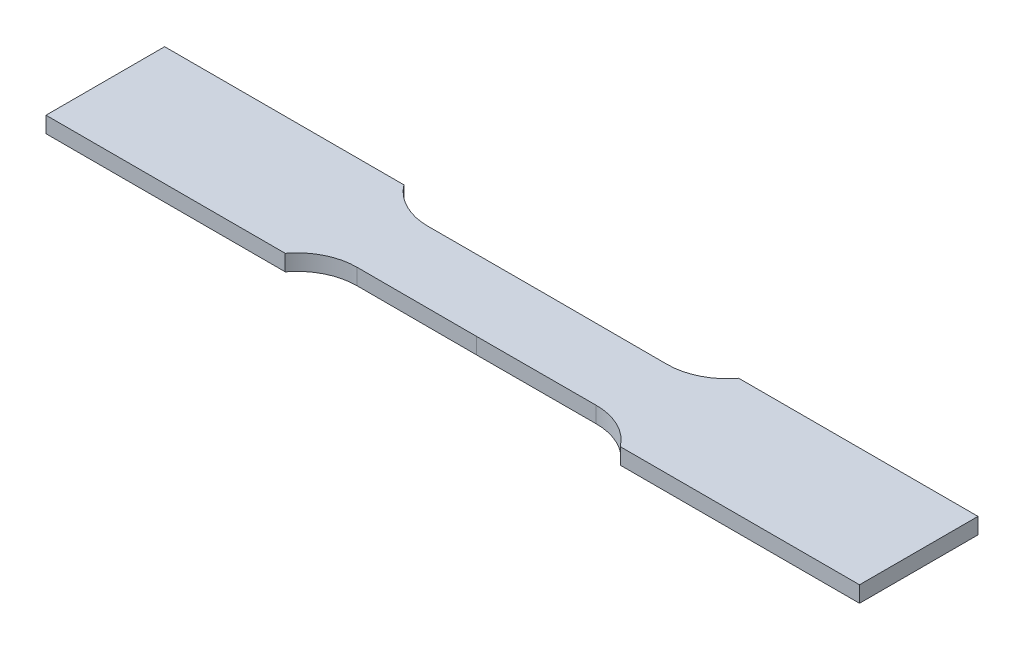
SolidWorks part; units mm, degrees
ref_plane "Front Plane" through (0, 0, 0) normal (0, 0, 1) x (1, 0, 0)
ref_plane "Top Plane" through (0, 0, 0) normal (0, 1, 0) x (1, 0, 0)
ref_plane "Right Plane" through (0, 0, 0) normal (1, 0, 0) x (0, 0, -1)
sketch "Sketch1" plane through (0, 0, 0) normal (0, 1, 0) x (1, 0, 0)
  line L3 (25, 7.405) -> (0, 7.44)
  line L4 (0, 7.44) -> (-25, 7.415)
  line L5 (-25, -7.415) -> (0, -7.44)
  line L6 (0, -7.44) -> (25, -7.405)
  line L7 (0, 7.44) -> (0, -7.44) construction
  line L8 (-25, 0) -> (25, 0) construction
  line L9 (25, 7.405) -> (25, 12.3817) construction
  line L10 (-35, 12.3984) -> (-25, 12.3984) construction
  line L11 (-25, 12.3984) -> (-25, 7.415) construction
  line L12 (-25, -12.3984) -> (-25, -7.415) construction
  line L13 (-35, 12.3984) -> (-85, 12.3984)
  line L15 (-35, -12.3984) -> (-85, -12.3984)
  line L16 (-85, 12.3984) -> (-85, -12.3984)
  line L17 (25, 12.3817) -> (35, 12.3817) construction
  line L18 (-35, -12.3984) -> (-25, -12.3984) construction
  line L19 (-25, 7.415) -> (-25, -7.415) construction
  line L20 (25, -7.405) -> (25, 7.405) construction
  line L22 (25, -7.405) -> (25, -12.3817) construction
  line L23 (25, -12.3817) -> (35, -12.3817) construction
  line L24 (35, 12.3817) -> (85, 12.3817)
  line L26 (35, -12.3817) -> (85, -12.3817)
  line L27 (85, 12.3817) -> (85, -12.3817)
  arc A0 (-35, 12.3984) -> (-25, 7.415) centre (-25.0125, 19.915) ccw
  arc A1 (-35, -12.3984) -> (-25, -7.415) centre (-25.0125, -19.915) cw
  arc A2 (35, -12.3817) -> (25, -7.405) centre (25.0175, -19.905) ccw
  arc A3 (35, 12.3817) -> (25, 7.405) centre (25.0175, 19.905) cw
  dimension "D5" = 25
  dimension "D9" = 25
  dimension "D4" = 14.88
  dimension "D6" = 10
  dimension "D8" = 50
  dimension "D1" = 14.83
  dimension "D2" = 14.81
  dimension "D3" = 50
  dimension "D10" = 10
  dimension "D11" = 50
extrude "Boss-Extrude2" add sketch "Sketch1" along normal blind 3.357 contours L24 A3 L3 L4 A0 L13 L16 L15 A1 L5 L6 A2 L26 L27
equation "\"D5@Sketch1\"=12.5*2"
equation "\"D9@Sketch1\"=12.5*2"
